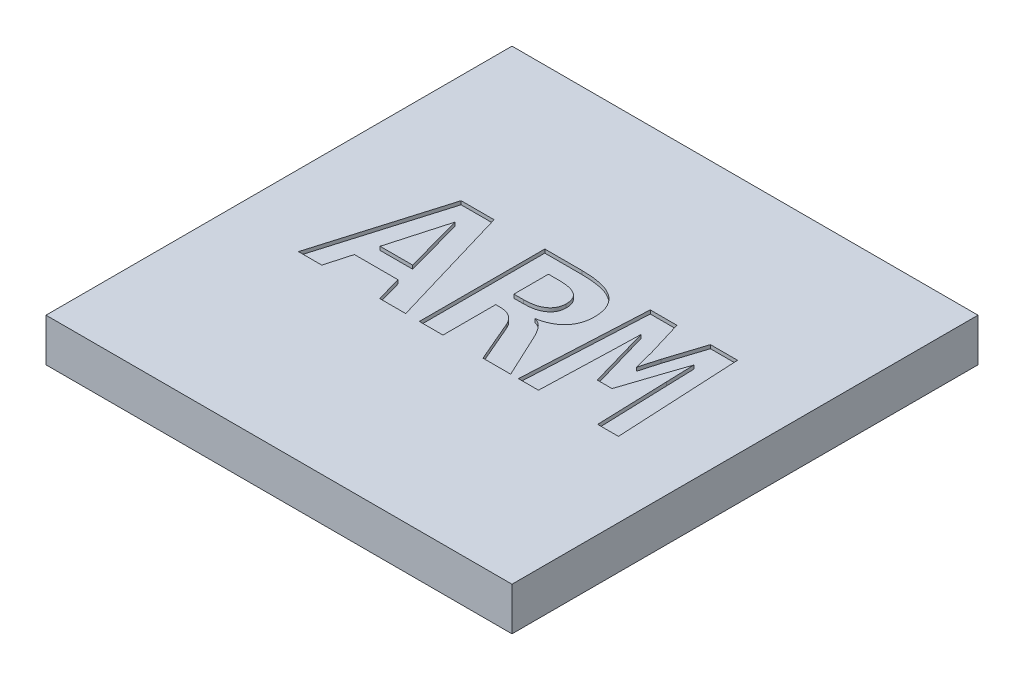
SolidWorks part; units mm, degrees
ref_plane "정면" through (0, 0, 0) normal (0, 0, 1) x (1, 0, 0)
ref_plane "윗면" through (0, 0, 0) normal (0, 1, 0) x (1, 0, 0)
ref_plane "우측면" through (0, 0, 0) normal (1, 0, 0) x (0, 0, -1)
sketch "스케치1" plane through (0, 0, 0) normal (0, 1, 0) x (1, 0, 0)
  line L1 (0, 0) -> (13, 0)
  line L2 (0, 0) -> (0, 13)
  line L3 (0, 13) -> (13, 13)
  line L4 (13, 0) -> (13, 13)
  dimension "D1" = 13
  dimension "D2" = 13
extrude "보스-돌출1" add sketch "스케치1" along normal blind 1.2
sketch "스케치2" plane through (0, 1.2, 0) normal (0, 1, 0) x (1, 0, 0)
  line L0 (0, 5.0563) -> (13, 5.0563) construction
  line L1 (0, 13) -> (0, 0) construction
  line L2 (13, 0) -> (13, 13) construction
  text T0 "ARM" font "Consolas" height 3.5
extrude "컷-돌출1" cut sketch "스케치2" against normal blind 0.1
